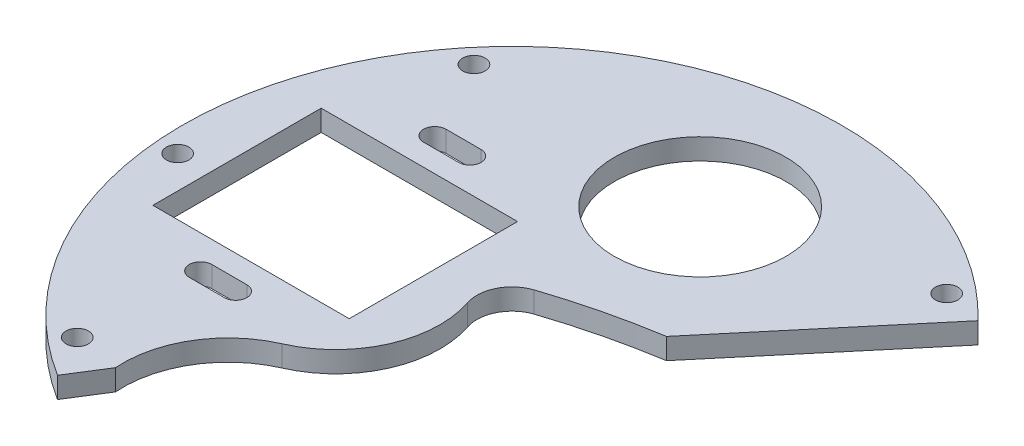
SolidWorks part; units mm, degrees
ref_plane "Front Plane" through (0, 0, 0) normal (0, 0, 1) x (1, 0, 0)
ref_plane "Top Plane" through (0, 0, 0) normal (0, 1, 0) x (1, 0, 0)
ref_plane "Right Plane" through (0, 0, 0) normal (1, 0, 0) x (0, 0, -1)
sketch "Sketch1" plane through (0, 0, 0) normal (0, 1, 0) x (1, 0, 0)
  line L0 (0, 0) -> (-28.2827, -33.706) construction
  line L1 (0, 0) -> (-33.706, 28.2827) construction
  line L2 (0, 0) -> (28.2827, 33.706) construction
  line L3 (-11.2046, 0) -> (0, 0) construction
  line L4 (13.5997, 8.4289) -> (33.8698, 32.5858)
  line L5 (-39.2046, 12) -> (-11.2046, 12)
  line L6 (-39.2046, 12) -> (-39.2046, -12)
  line L7 (-39.2046, -12) -> (-11.2046, -12)
  line L8 (-11.2046, 12) -> (-11.2046, -12)
  line L9 (0, 0) -> (-43.8326, -3.8349) construction
  line L10 (26.2094, 39.0137) -> (22.3274, 34.3873)
  line L11 (-27.7046, 16.7) -> (-22.7046, 16.7) construction
  line L12 (-27.7046, 18.3) -> (-22.7046, 18.3)
  line L13 (-27.7046, 15.1) -> (-22.7046, 15.1)
  line L14 (-39.2046, 0) -> (-11.2046, 0) construction
  line L15 (-21.8252, -34.7082) -> (-25.0192, -39.7875)
  line L16 (-25.2046, 16.7) -> (-25.2046, 0) construction
  line L17 (-27.7046, -16.7) -> (-22.7046, -16.7) construction
  line L18 (-27.7046, -18.3) -> (-22.7046, -18.3)
  line L19 (-27.7046, -15.1) -> (-22.7046, -15.1)
  arc A0 (33.8698, 32.5858) -> (-25.0192, -39.7875) centre (0, 0) ccw
  circle A1 centre (28.2827, 33.706) radius 1.6
  circle A2 centre (-33.706, 28.2827) radius 1.6
  circle A3 centre (-28.2827, -33.706) radius 1.6
  circle A4 centre (0, 0) radius 5
  arc A6 (22.3274, 34.3873) -> (29.9878, 27.9595) centre (0, 0) ccw
  circle A7 centre (-43.8326, -3.8349) radius 1.6
  arc A8 (13.5997, 8.4289) -> (-1.5702, 4.747) centre (28.5974, -86.4561) ccw
  arc A9 (-12.8925, -19.8797) -> (-21.8252, -34.7082) centre (-6.8651, -33.6154) ccw
  circle A10 centre (0, 26.835) radius 12.2474
  arc A11 (-12.8925, -19.8797) -> (-4.7463, -1.5726) centre (-18.8721, -6.2529) ccw
  arc A12 (-27.7046, 18.3) -> (-27.7046, 15.1) centre (-27.7046, 16.7) ccw
  arc A13 (-22.7046, 15.1) -> (-22.7046, 18.3) centre (-22.7046, 16.7) ccw
  arc A14 (-27.7046, -18.3) -> (-27.7046, -15.1) centre (-27.7046, -16.7) cw
  arc A15 (-22.7046, -15.1) -> (-22.7046, -18.3) centre (-22.7046, -16.7) cw
  point P30 (-25.2046, 16.7)
  point P43 (-25.2046, -16.7)
  dimension "D3" = 47
  dimension "D7" = 3.2
  dimension "D8" = 3.2
  dimension "D9" = 3.2
  dimension "D10" = 10
  dimension "D11" = 28
  dimension "D15" = 82
  dimension "D18" = 3.2
  dimension "D20" = 1.6
  dimension "D22" = 15
  dimension "D1" = 90
  dimension "D2" = 90
  dimension "D4" = 44
  dimension "D5" = 44
  dimension "D6" = 44
  dimension "D12" = 5
  dimension "D13" = 5
  dimension "D16" = 44
  dimension "D14" = 24
  dimension "D17" = 45
  dimension "D19" = 16.7
  dimension "D21" = 5
extrude "Boss-Extrude1" add sketch "Sketch1" along normal blind 3
